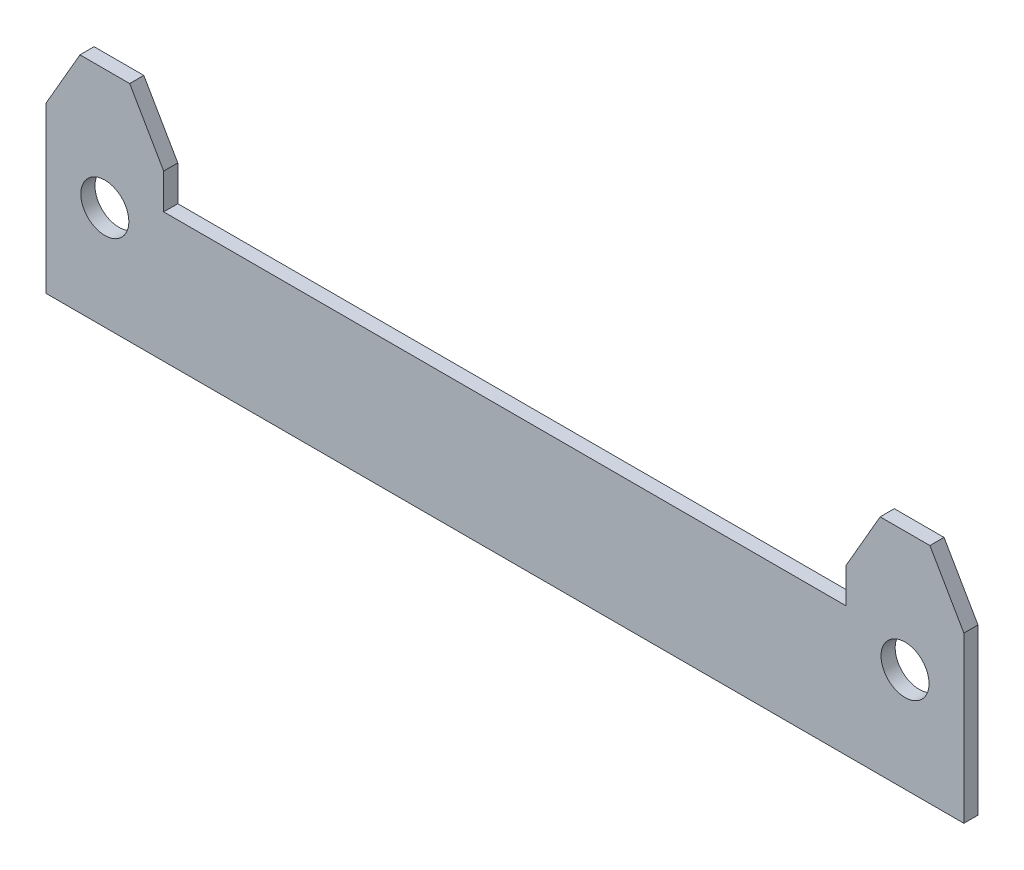
SolidWorks part; units mm, degrees
material "PMMA"
ref_plane "Płaszczyzna przednia" through (0, 0, 0) normal (0, 0, 1) x (1, 0, 0)
ref_plane "Płaszczyzna górna" through (0, 0, 0) normal (0, 1, 0) x (1, 0, 0)
ref_plane "Płaszczyzna prawa" through (0, 0, 0) normal (1, 0, 0) x (0, 0, -1)
sketch "Szkic1" plane through (0, 0, 0) normal (0, 0, 1) x (1, 0, 0)
  line L0 (97.5, 0) -> (-97.5, 0)
  line L1 (-97.5, 0) -> (-97.5, 35)
  line L2 (-97.5, 35) -> (-90.2831, 47.5)
  line L3 (-90.2831, 47.5) -> (-79.7169, 47.5)
  line L4 (-79.7169, 47.5) -> (-72.5, 35)
  line L5 (-72.5, 35) -> (-72.5, 27.5)
  line L6 (-72.5, 27.5) -> (72.5, 27.5)
  line L7 (0, 0) -> (0, 27.5) construction
  line L8 (-85, 0) -> (-85, 22) construction
  line L9 (72.5, 35) -> (72.5, 27.5)
  line L10 (79.7169, 47.5) -> (72.5, 35)
  line L11 (90.2831, 47.5) -> (79.7169, 47.5)
  line L12 (97.5, 35) -> (90.2831, 47.5)
  line L13 (97.5, 0) -> (97.5, 35)
  circle A0 centre (-85, 22) radius 5.1
  circle A1 centre (85, 22) radius 5.1
  dimension "D1" = 170
  dimension "D4" = 10.2
  dimension "D2" = 22
  dimension "D3" = 25
  dimension "D5" = 47.5
  dimension "D6" = 60
  dimension "D7" = 35
  dimension "D8" = 27.5
extrude "Dodanie-wyciągnięcie1" add sketch "Szkic1" along normal blind 3
